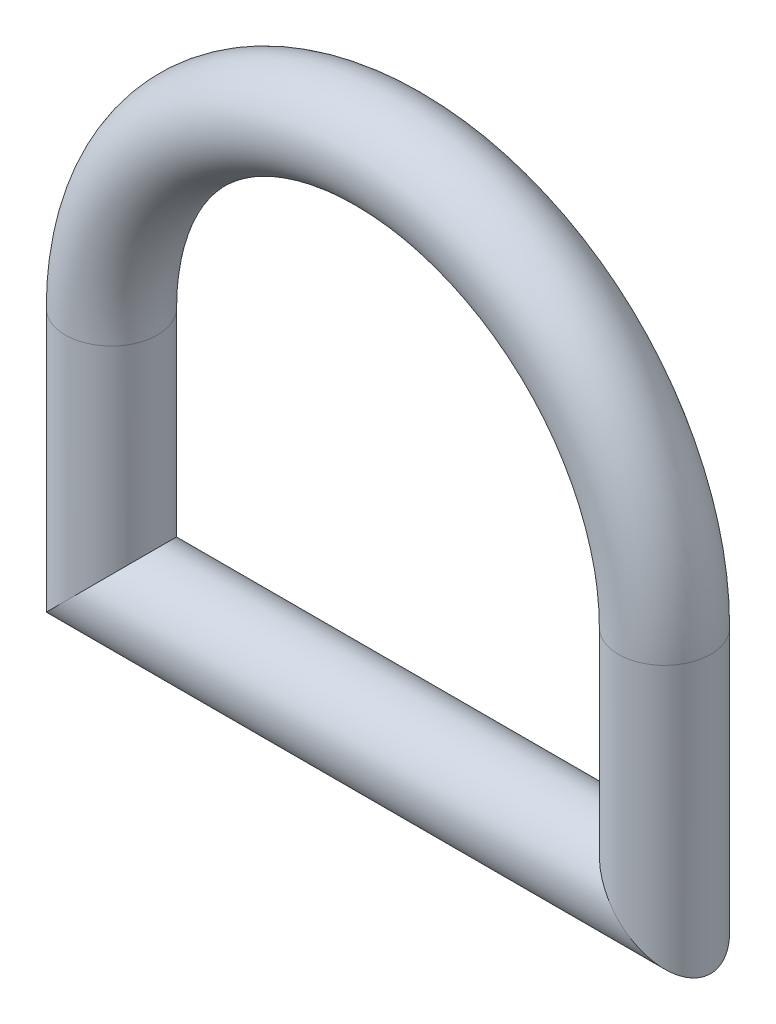
SolidWorks part; units mm, degrees
material "Plain Carbon Steel"
ref_plane "Front" through (0, 0, 0) normal (0, 0, 1) x (1, 0, 0)
ref_plane "Top" through (0, 0, 0) normal (0, 1, 0) x (1, 0, 0)
ref_plane "Right" through (0, 0, 0) normal (1, 0, 0) x (0, 0, -1)
sketch "Sketch1" plane through (0, 0, 0) normal (0, 0, 1) x (1, 0, 0)
  line L0 (0, 0) -> (19.05, 0)
  line L1 (50, 0) -> (-50, 0) construction
  line L2 (19.05, 0) -> (19.05, 15.875)
  line L3 (0, 0) -> (-19.05, 0)
  line L4 (-19.05, 0) -> (-19.05, 15.875)
  line L5 (-19.05, 15.875) -> (0, 15.875) construction
  line L6 (0, 15.875) -> (19.05, 15.875) construction
  arc A0 (-19.05, 15.875) -> (19.05, 15.875) centre (0, 15.875) cw
  point P9 (0, 34.925)
  dimension "D2" = 34.925
  dimension "D1" = 38.1
sketch "Sketch2" plane through (0, 0, 0) normal (0, 1, 0) x (1, 0, 0)
  circle A0 centre (19.05, 0) radius 3.175
  dimension "D1" = 6.35
sweep "Sweep1" add profiles "Sketch2" path "Sketch1"
